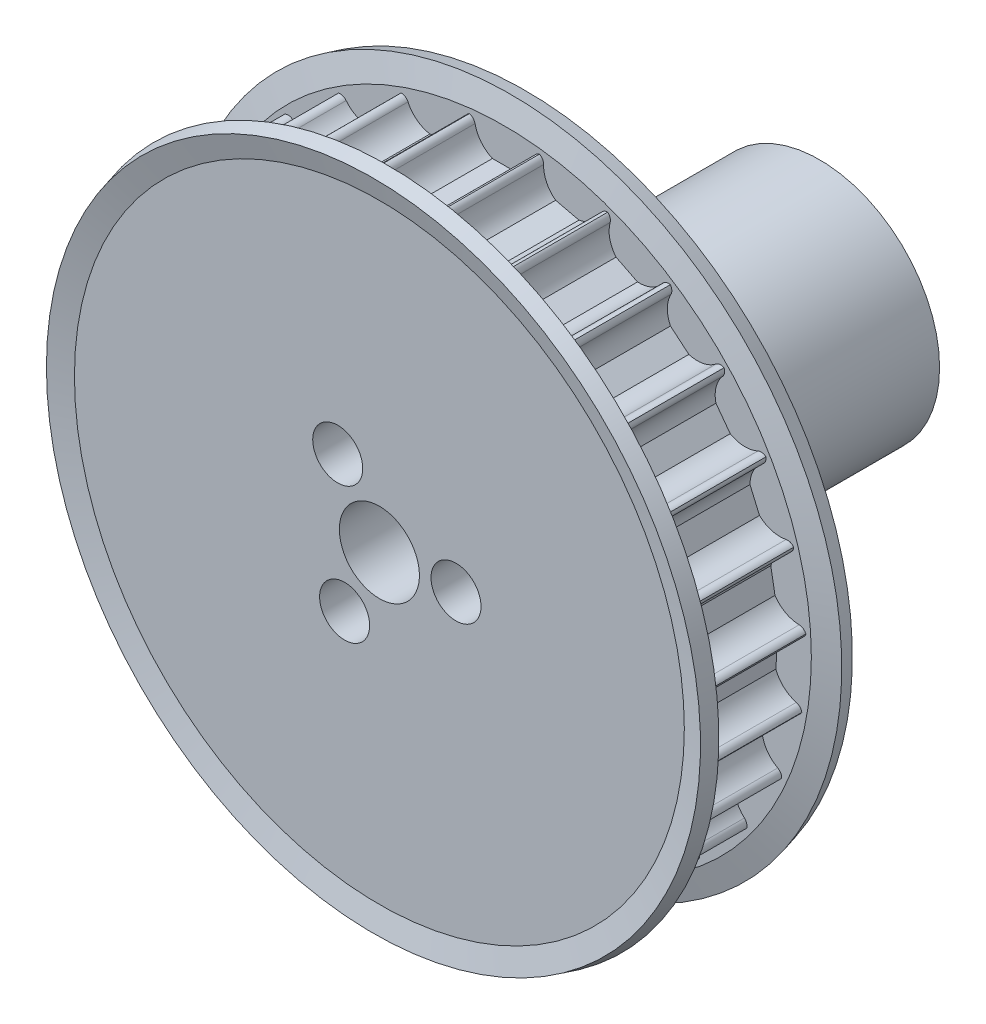
SolidWorks part; units mm, degrees
ref_plane "Front Plane" through (0, 0, 0) normal (0, 0, 1) x (1, 0, 0)
ref_plane "Top Plane" through (0, 0, 0) normal (0, 1, 0) x (1, 0, 0)
ref_plane "Right Plane" through (0, 0, 0) normal (1, 0, 0) x (0, 0, -1)
ref_axis "Axis1" through (0, 0, -88.99) along (0, 0, 1)
sketch "Sketch1" plane through (0, 0, 0) normal (1, 0, 0) x (0, 0, -1)
  line L0 (0, 4) -> (0, 31)
  line L1 (0, 31) -> (14, 31)
  line L2 (14, 31) -> (14, 12)
  line L3 (14, 12) -> (44, 12)
  line L4 (44, 12) -> (44, 4)
  line L5 (44, 4) -> (0, 4)
  line L6 (88.99, 0) -> (-88.99, 0) construction
  dimension "D1" = 30
  dimension "D2" = 31
  dimension "D3" = 12
  dimension "D4" = 14
  dimension "D5" = 4
revolve "Revolve1" add sketch "Sketch1" angle 360 about axis through (0, 0, -88.99) along (0, 0, 1)
sketch "Sketch2" plane through (0, 0, 0) normal (0, 0, 1) x (1, 0, 0)
  line L0 (3.6742, 30) -> (3.75, 30)
  line L1 (-3.75, 30) -> (-3.6742, 30)
  line L2 (-3.75, 30) -> (-3.75, 32)
  line L3 (-3.75, 32) -> (3.75, 32)
  line L4 (3.75, 30) -> (3.75, 32)
  line L5 (-1.199, 27.25) -> (1.199, 27.25)
  arc A0 (-2.9394, 29.4) -> (-1.199, 27.25) centre (0, 30) ccw
  arc A1 (-2.9394, 29.4) -> (-3.6742, 30) centre (-3.6742, 29.25) ccw
  arc A2 (2.9394, 29.4) -> (3.6742, 30) centre (3.6742, 29.25) cw
  arc A3 (1.199, 27.25) -> (2.9394, 29.4) centre (0, 30) ccw
  point P13 (-3, 30)
  point P16 (3, 30)
  dimension "D1" = 3
  dimension "D5" = 0.75
  dimension "D6" = 0.75
  dimension "D2" = 2
  dimension "D3" = 7.5
  dimension "D4" = 30
  dimension "D7" = 2.75
extrude "Cut-Extrude1" cut sketch "Sketch2" against normal through all
pattern_circular "CirPattern1" count 27 over 360 about axis through (0, 0, 0) along (0, 0, 1) of "Cut-Extrude1"
sketch "Sketch3" plane through (0, 0, 0) normal (1, 0, 0) x (0, 0, -1)
  line L0 (0, 29.2854) -> (0, 26.792) construction
  line L1 (0, 27.2415) -> (1.5, 27.2415)
  line L2 (0, 27.2415) -> (0, 30.6805)
  line L3 (0, 30.6805) -> (1.5, 30.6805) construction
  line L4 (1.5, 27.2415) -> (1.5, 30.6805)
  line L5 (1.5, 30.6805) -> (0.0511, 30.2922) construction
  line L6 (1.5, 30.6805) -> (0.8569, 33.0805)
  line L7 (0.0511, 30.2922) -> (-0.592, 32.6922)
  line L8 (0.8569, 33.0805) -> (-0.592, 32.6922)
  line L9 (7, 39.7867) -> (7, -33.9897) construction
  line L10 (12.5, 30.6805) -> (13.9489, 30.2922) construction
  line L11 (14, 30.6805) -> (12.5, 30.6805) construction
  line L12 (13.1431, 33.0805) -> (14.592, 32.6922)
  line L13 (13.9489, 30.2922) -> (14.592, 32.6922)
  line L14 (12.5, 30.6805) -> (13.1431, 33.0805)
  line L15 (12.5, 27.2415) -> (12.5, 30.6805)
  line L16 (14, 27.2415) -> (14, 30.6805)
  line L17 (14, 27.2415) -> (12.5, 27.2415)
  line L18 (0, 28.3642) -> (0, 27.592) construction
  line L19 (0, 27.592) -> (0, 24.8896) construction
  dimension "D1" = 1.5
  dimension "D2" = 1.5
  dimension "D3" = 2.4
  dimension "D4" = 165
  dimension "D5" = 0.7
revolve "Revolve3" add sketch "Sketch3" angle 360 about axis through (0, 0, -88.99) along (0, 0, 1)
sketch "Sketch4" plane through (0, 0, -44) normal (0, 0, -1) x (-1, 0, 0)
  circle A0 centre (-7.66, 0.399) radius 2.5
  circle A1 centre (4.1649, 6.4288) radius 2.5
  circle A2 centre (3.4744, -6.8267) radius 2.5
  dimension "D1" = 5
  dimension "D3" = 7.66
  dimension "D4" = 7.66
  dimension "D5" = 7.66
  dimension "D2" = 3
extrude "Cut-Extrude2" cut sketch "Sketch4" against normal through all
ref_plane "Plane1" through (0, 0, -7) normal (0, 0, 1) x (1, 0, 0)
sketch "Sketch5" plane through (0, 0, -7) normal (0, 0, 1) x (1, 0, 0)
  circle A0 centre (0, 0) radius 32
  dimension "D1" = 64
